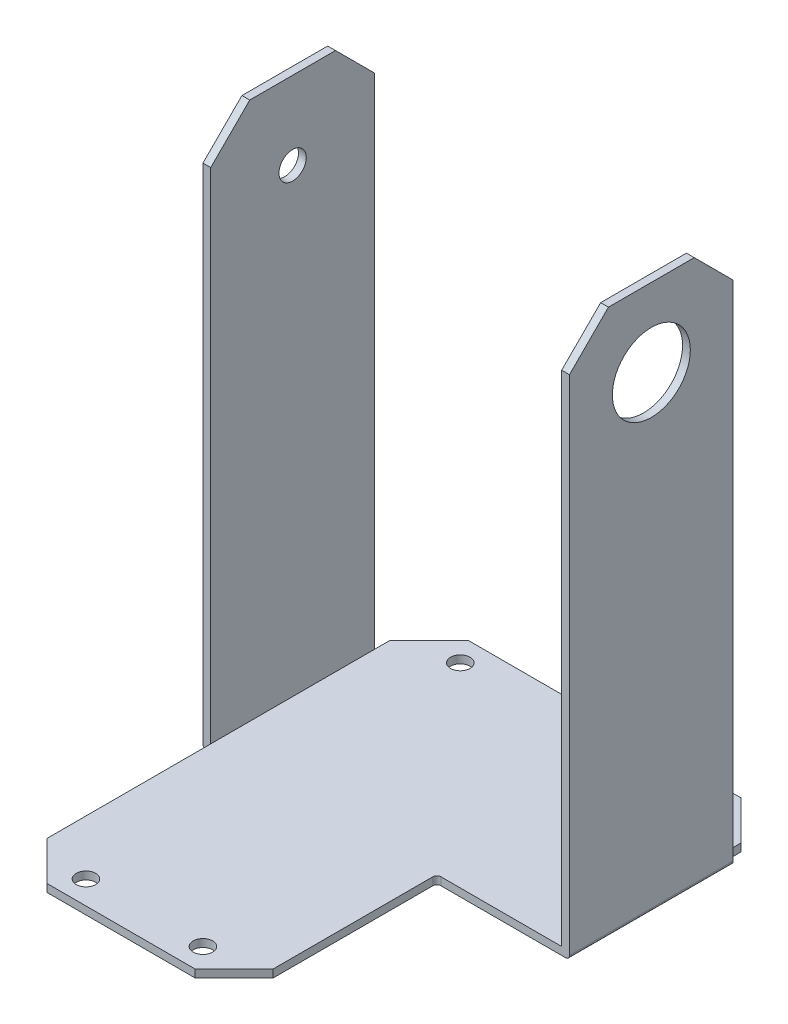
SolidWorks part; units mm, degrees
ref_plane "前视基准面" through (0, 0, 0) normal (0, 0, 1) x (1, 0, 0)
ref_plane "上视基准面" through (0, 0, 0) normal (0, 1, 0) x (1, 0, 0)
ref_plane "右视基准面" through (0, 0, 0) normal (1, 0, 0) x (0, 0, -1)
sketch "草图1" plane through (0, 0, 0) normal (0, 1, 0) x (1, 0, 0)
  line L0 (0, 0) -> (-47, 0)
  line L1 (-47, 0) -> (-47, 21)
  line L2 (-47, 21) -> (0, 21)
  line L3 (0, 21) -> (0, 0)
  dimension "D1" = 47
  dimension "D2" = 21
extrude "凸台-拉伸1" add sketch "草图1" along normal blind 70
shell "抽壳1" thickness 1
sketch "草图2" plane through (0, 0, 0) normal (0, 0, 1) x (1, 0, 0)
  line L0 (-46, 1) -> (-46, 0)
  line L1 (-47, 0) -> (0, 0) construction
  line L2 (-46, 0) -> (-17, 0)
  line L3 (-17, 0) -> (-17, 1)
  line L4 (-46, 1) -> (-1, 1) construction
  line L5 (-17, 1) -> (-46, 1)
  dimension "D1" = 29
extrude "凸台-拉伸2" add sketch "草图2" along normal blind 26
sketch "草图3" plane through (0, 0, -21) normal (0, 0, -1) x (-1, 0, 0)
  line L0 (1, 1) -> (1, 0)
  line L1 (0, 0) -> (47, 0) construction
  line L2 (1, 0) -> (46, 0)
  line L3 (46, 0) -> (46, 1)
  line L4 (46, 1) -> (1, 1)
extrude "凸台-拉伸3" add sketch "草图3" along normal blind 7
hole_wizard "Ø10.0 (10) 直径槽口1" positions "草图4" profile "草图5" size "Ø10.0" standard "GB"
sketch "草图4" plane through (0, 0, 0) normal (1, 0, 0) x (0, 0, -1)
  line L0 (0, 70) -> (21, 70) construction
  line L2 (21, 70) -> (21, 0) construction
  point P0 (10.5, 60)
  point P9 (21, 59.1408)
  dimension "D1" = 10
  dimension "D2" = 10.5
sketch "草图5" plane through (0, 60, -10.5) normal (0, 1, 0) x (0, 0, -1)
  line L0 (0, 0) -> (0, 1)
  line L1 (0, 1) -> (5, 1)
  line L2 (5, 1) -> (5, 0)
  line L5 (5, 0) -> (0, 0)
  line L11 (0, -6.35) -> (0, 107.95) construction
  dimension "通孔孔直径" = 10
  dimension "通孔孔深度" = 1
hole_wizard "Ø3.5 (3.5) 直径槽口1" positions "草图6" profile "草图7" size "Ø3.5" standard "GB" slot yes end condition up to next
sketch "草图6" plane through (-47, 0, 0) normal (-1, 0, 0) x (0, 0, 1)
  line L0 (-21, 70) -> (0, 70) construction
  point P0 (-10.5, 60)
  point P9 (-12.0676, 60)
  point P12 (0, 0)
  point P13 (-10.5, 70)
  dimension "D1" = 10
sketch "草图7" plane through (-47, 60, -10.5) normal (0, 1, 0) x (0, 0, 1)
  line L0 (0, 0) -> (0, 1)
  line L1 (0, 1) -> (1.75, 1)
  line L2 (1.75, 1) -> (1.75, 0)
  line L5 (1.75, 0) -> (0, 0)
  line L11 (0, -6.35) -> (0, 107.95) construction
  dimension "通孔孔直径" = 3.5
  dimension "通孔孔深度" = 1
hole_wizard "M3 螺纹孔1" positions "草图8" profile "草图10" tap size "M3" standard "IS" end condition up to next
sketch "草图8" plane through (0, 1, 0) normal (0, 1, 0) x (1, 0, 0)
  line L0 (-17, -26) -> (-46, -26) construction
  line L1 (-46, 28) -> (-1, 28) construction
  line L2 (-46, -26) -> (-46, 0) construction
  line L3 (-17, -26) -> (-17, 0) construction
  point P0 (-39, -23)
  point P2 (-24, -23)
  point P4 (-24, 25)
  point P6 (-39, 25)
  point P17 (0, 0)
  point P18 (0, 0)
  dimension "D1" = 3
  dimension "D2" = 3
  dimension "D3" = 3
  dimension "D4" = 3
  dimension "D5" = 7
  dimension "D6" = 7
sketch "草图10" plane through (-39, 1, 23) normal (1, 0, 0) x (0, 0, 1)
  line L0 (0, 0) -> (0, 1)
  line L1 (0, 1) -> (1.25, 1)
  line L2 (1.25, 1) -> (1.25, 0)
  line L5 (1.25, 0) -> (0, 0)
  line L11 (0, -6.35) -> (0, 107.95) construction
  dimension "通孔螺纹孔钻头直径" = 2.5
  dimension "通孔螺纹孔钻头深度" = 1
cosmetic thread "孔螺蚊线1" parameters "D2"=3
cosmetic thread "孔螺蚊线2" parameters "D2"=3
cosmetic thread "孔螺蚊线3" parameters "D2"=3
cosmetic thread "孔螺蚊线4" parameters "D2"=3
chamfer "倒角1" distance 5 8 edges at (-1, 0.5, -28) (-46, 0.5, -28) (-46, 0.5, 26) (-17, 0.5, 26) (-0.5, 70, -21) (-0.5, 70, 0) (-46.5, 70, -21) (-46.5, 70, 0)
fillet "圆角1" radius 0.5 3 edges at (-17, 0.5, 0) (-47, 0, -10.5) (0, 0, -10.5)
